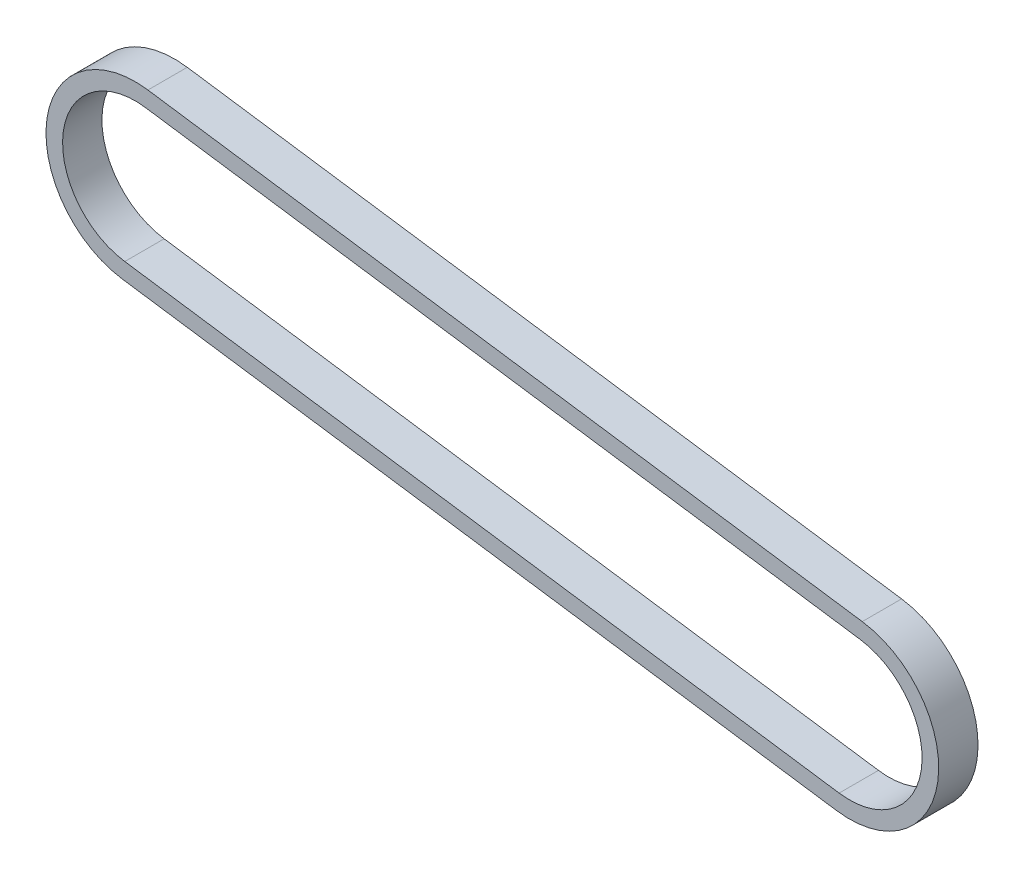
SolidWorks part; units mm, degrees
material "NEOPRENE"
ref_plane "Front Plane" through (0, 0, 0) normal (0, 0, 1) x (1, 0, 0)
ref_plane "Top Plane" through (0, 0, 0) normal (0, 1, 0) x (1, 0, 0)
ref_plane "Right Plane" through (0, 0, 0) normal (1, 0, 0) x (0, 0, -1)
ref_plane "Plane1" through (0, 0, 48.6875) normal (0, 0, -1) x (-1, 0, 0)
sketch "Sketch2" plane through (0, 0, 0) normal (0, 0, -1) x (-1, 0, 0)
  line L0 (74.3354, 10.7381) -> (-89.0686, -12.8663) construction
  line L1 (76.9803, -7.5719) -> (-86.4236, -31.1763) construction
  line L2 (71.6904, 29.048) -> (-91.7135, 5.4436) construction
  line L3 (77.252, -9.4524) -> (-86.152, -33.0568)
  line L4 (71.4188, 30.9285) -> (-91.9852, 7.3241)
  line L5 (76.7087, -5.6914) -> (-86.6953, -29.2958)
  line L6 (71.9621, 27.1675) -> (-91.4419, 3.5631)
  circle A2 centre (-89.0686, -12.8663) radius 18.5 construction
  circle A3 centre (74.3354, 10.7381) radius 18.5 construction
  arc A4 (76.9803, -7.5719) -> (71.6904, 29.048) centre (74.3354, 10.7381) ccw construction
  arc A5 (-91.7135, 5.4436) -> (-86.4236, -31.1763) centre (-89.0686, -12.8663) ccw construction
  arc A6 (-91.9852, 7.3241) -> (-86.152, -33.0568) centre (-89.0686, -12.8663) ccw
  arc A7 (77.252, -9.4524) -> (71.4188, 30.9285) centre (74.3354, 10.7381) ccw
  arc A8 (-91.4419, 3.5631) -> (-86.6953, -29.2958) centre (-89.0686, -12.8663) ccw
  arc A9 (76.7087, -5.6914) -> (71.9621, 27.1675) centre (74.3354, 10.7381) ccw
  point P6 (-7.3666, -1.0641)
  dimension "D2" = 1.9
  dimension "D3" = 1.9
extrude "Boss-Extrude1" add sketch "Sketch2" along normal mid plane 9
